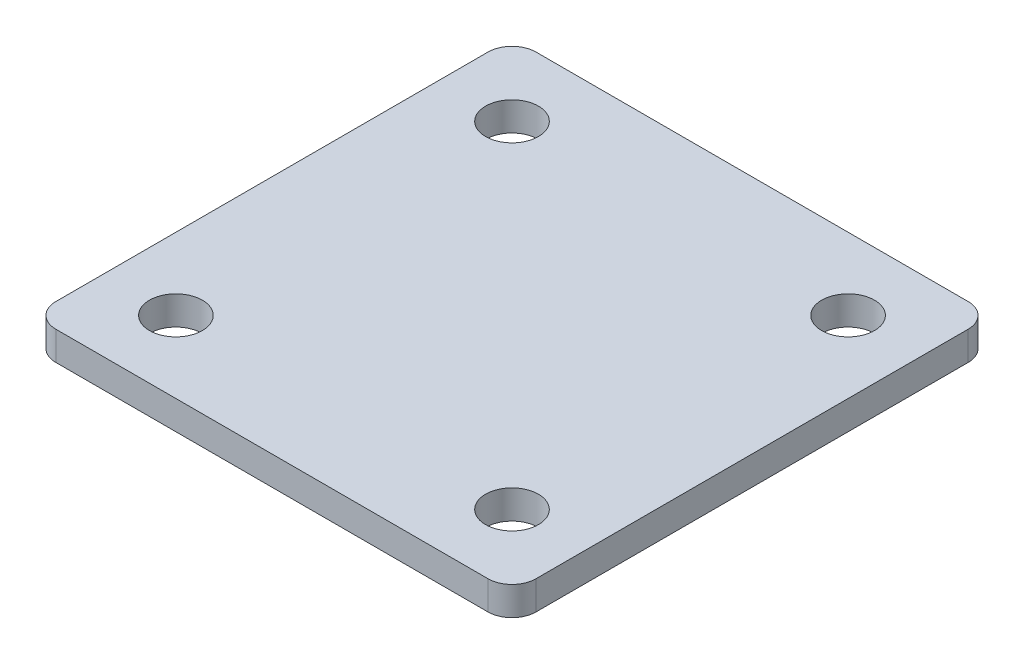
SolidWorks part; units mm, degrees
ref_plane "Front Plane" through (0, 0, 0) normal (0, 0, 1) x (1, 0, 0)
ref_plane "Top Plane" through (0, 0, 0) normal (0, 1, 0) x (1, 0, 0)
ref_plane "Right Plane" through (0, 0, 0) normal (1, 0, 0) x (0, 0, -1)
sketch "Sketch1" plane through (0, 0, 0) normal (0, 1, 0) x (1, 0, 0)
  line L1 (-50, 50) -> (50, 50)
  line L2 (-50, 50) -> (-50, -50)
  line L3 (-50, -50) -> (50, -50)
  line L4 (50, 50) -> (50, -50)
  line L5 (-50, 50) -> (50, -50) construction
  line L6 (-50, -50) -> (50, 50) construction
  point P0 (0, 0)
  dimension "D1" = 100
  dimension "D2" = 100
extrude "Boss-Extrude1" add sketch "Sketch1" along normal blind 6
sketch "Sketch3" plane through (0, 6, 0) normal (0, 1, 0) x (1, 0, 0)
  line L0 (0, 50) -> (0, -50) construction
  line L1 (50, 50) -> (-50, 50) construction
  line L2 (-50, -50) -> (50, -50) construction
  line L3 (-50, 0) -> (50, 0) construction
  line L4 (-50, 50) -> (-50, -50) construction
  line L5 (50, -50) -> (50, 50) construction
  point P12 (-35, 35)
  point P13 (35, 35)
  point P14 (35, -35)
  point P15 (-35, -35)
  point P16 (0, 0)
  point P17 (0, 0)
  point P18 (0, 0)
  point P19 (-38.0181, 40.0806)
  dimension "D1" = 70
  dimension "D2" = 70
hole_wizard "M10 Clearance Hole1" positions "3DSketch2" profile "Sketch4" hole size "M10" standard "ANSI Metric"
sketch3d "3DSketch2"
  point P0 (-35, 6, -35)
  point P3 (35, 6, -35)
  point P6 (35, 6, 35)
  point P9 (-35, 6, 35)
sketch "Sketch4" plane through (-35, 6, -35) normal (1, 0, 0) x (0, 0, 1)
  line L0 (0, 0) -> (0, 23.0547)
  line L1 (0, 23.0547) -> (5.5, 19.75)
  line L2 (5.5, 19.75) -> (5.5, 0)
  line L5 (5.5, 0) -> (0, 0)
  line L10 (0, 23.0547) -> (-5.5, 19.75) construction
  line L11 (0, -6.35) -> (0, 107.95) construction
  dimension "Hole Dia." = 11
  dimension "Hole Depth" = 19.75
  dimension "Drill Angle" = 118
fillet "Fillet1" radius 5 4 edges at (-50, 3, 50) (50, 3, 50) (50, 3, -50) (-50, 3, -50)
